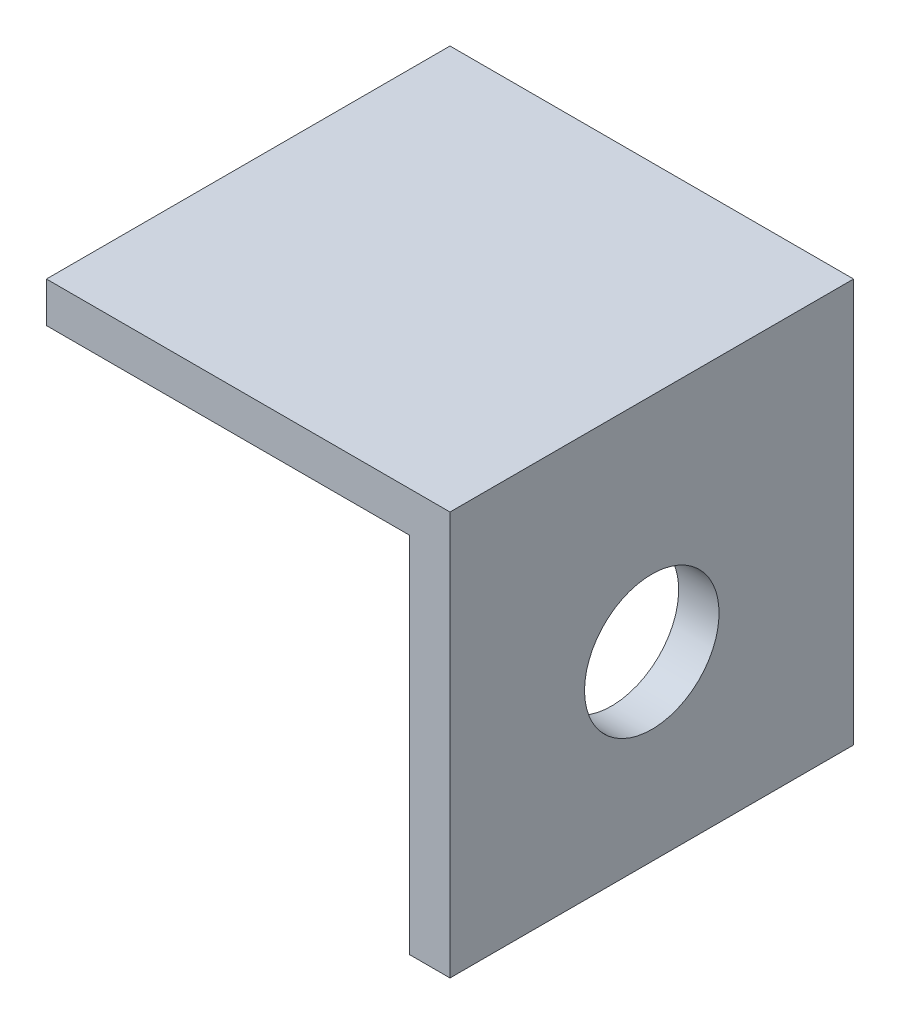
SolidWorks part; units mm, degrees
material "1.0037 (S235JR)"
ref_plane "Plan de face" through (0, 0, 0) normal (0, 0, 1) x (1, 0, 0)
ref_plane "Plan de dessus" through (0, 0, 0) normal (0, 1, 0) x (1, 0, 0)
ref_plane "Plan de droite" through (0, 0, 0) normal (1, 0, 0) x (0, 0, -1)
sketch "Esquisse1" plane through (0, 0, 0) normal (0, 0, 1) x (1, 0, 0)
  line L0 (0, 0) -> (0, -30)
  line L1 (0, -30) -> (-3, -30)
  line L2 (-3, -30) -> (-3, -3)
  line L3 (-3, -3) -> (-30, -3)
  line L4 (-30, -3) -> (-30, 0)
  line L5 (-30, 0) -> (0, 0)
  dimension "D1" = 30
  dimension "D2" = 30
  dimension "D3" = 3
  dimension "D4" = 3
extrude "Boss.-Extru.1" add sketch "Esquisse1" against normal blind 30
hole_wizard "Dégagement M81" positions "Esquisse2" profile "Esquisse3" hole size "M8" standard "ISO" end condition through all
sketch "Esquisse2" plane through (-3, -21, 985) normal (-1, 0, 0) x (0, -1, 0)
  line L1 (-18, 1015) -> (9, 1015) construction
  point P0 (-4.5, 1000)
  point P17 (-4.5, -1000)
  point P21 (-4.5, -1000)
sketch "Esquisse3" plane through (-3, -16.5, 1985) normal (0, 1, 0) x (0, 0, 1)
  line L0 (0, 0) -> (0, 3)
  line L1 (0, 3) -> (5, 3)
  line L2 (5, 3) -> (5, 0)
  line L3 (5, 0) -> (0, 0)
  line L4 (0, -6.35) -> (0, 107.95) construction
  dimension "Diamètre du perçage jusqu'au prochain" = 10
  dimension "Profondeur du perçage jusqu'au prochain" = 3
hole_wizard "Dégagement M82" positions "Esquisse4" profile "Esquisse5" hole size "M8" standard "ISO" end condition through all
sketch "Esquisse4" plane through (33, -21, -1015) normal (1, 0, 0) x (0, -1, 0)
  line L1 (-18, 1015) -> (9, 1015) construction
  point P0 (-4.5, 1000)
  point P17 (-4.5, -1000)
  point P21 (-4.5, -1000)
sketch "Esquisse5" plane through (33, -16.5, -2015) normal (0, 1, 0) x (0, 0, -1)
  line L0 (0, 0) -> (0, 63)
  line L1 (0, 63) -> (5, 63)
  line L2 (5, 63) -> (5, 0)
  line L3 (5, 0) -> (0, 0)
  line L4 (0, -6.35) -> (0, 107.95) construction
  dimension "Diamètre du perçage jusqu'au prochain" = 10
  dimension "Profondeur du perçage jusqu'au prochain" = 63
hole_wizard "Dégagement M83" positions "Esquisse6" profile "Esquisse7" hole size "M8" standard "ISO" end condition through all
sketch "Esquisse6" plane through (33, -21, 985) normal (1, 0, 0) x (0, -1, 0)
  line L1 (-18, 1015) -> (9, 1015) construction
  point P0 (-4.5, 1000)
  point P17 (-4.5, -1000)
  point P21 (-4.5, -1000)
sketch "Esquisse7" plane through (33, -16.5, -15) normal (0, 1, 0) x (0, 0, -1)
  line L0 (0, 0) -> (0, 63)
  line L1 (0, 63) -> (5, 63)
  line L2 (5, 63) -> (5, 0)
  line L3 (5, 0) -> (0, 0)
  line L4 (0, -6.35) -> (0, 107.95) construction
  dimension "Diamètre du perçage jusqu'au prochain" = 10
  dimension "Profondeur du perçage jusqu'au prochain" = 63
hole_wizard "Dégagement M84" positions "Esquisse8" profile "Esquisse9" hole size "M8" standard "ISO" end condition through all
sketch "Esquisse8" plane through (-3, -21, -1015) normal (-1, 0, 0) x (0, -1, 0)
  line L1 (-18, 1015) -> (9, 1015) construction
  point P0 (-4.5, 1000)
  point P17 (-4.5, -1000)
  point P21 (-4.5, -1000)
sketch "Esquisse9" plane through (-3, -16.5, -15) normal (0, 1, 0) x (0, 0, 1)
  line L0 (0, 0) -> (0, 3)
  line L1 (0, 3) -> (5, 3)
  line L2 (5, 3) -> (5, 0)
  line L3 (5, 0) -> (0, 0)
  line L4 (0, -6.35) -> (0, 107.95) construction
  dimension "Diamètre du perçage jusqu'au prochain" = 10
  dimension "Profondeur du perçage jusqu'au prochain" = 3
